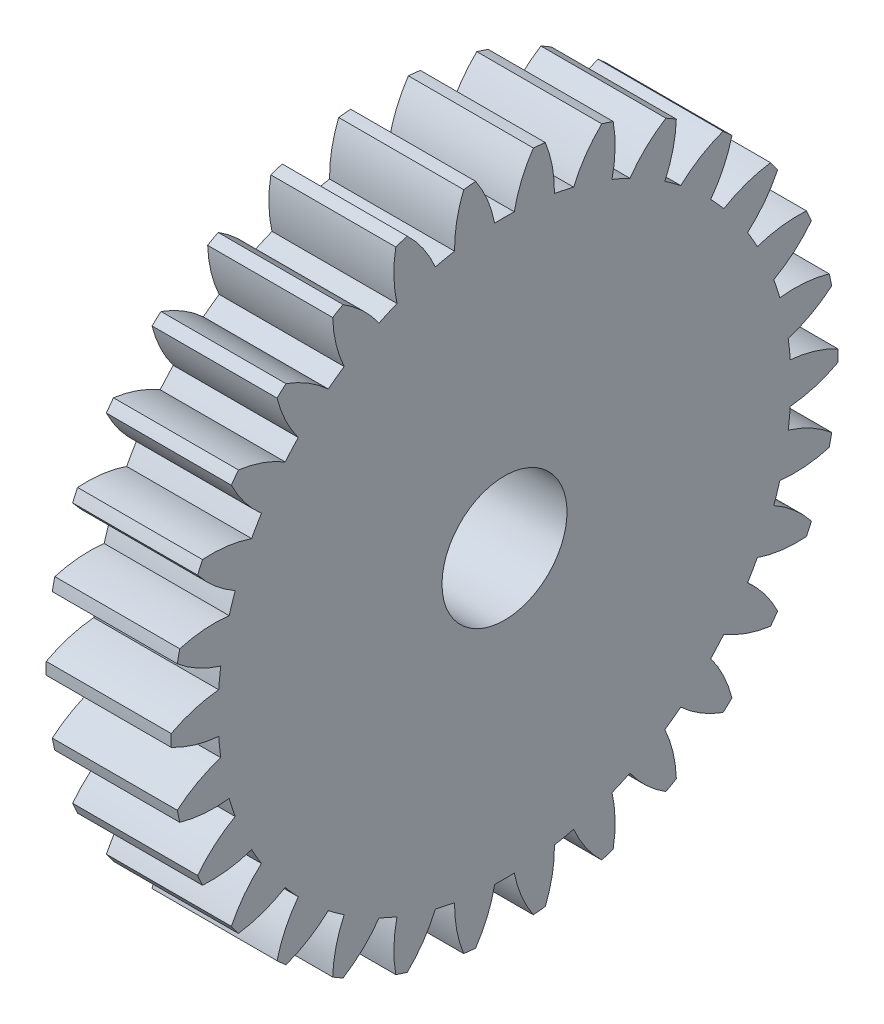
SolidWorks part; units mm, degrees
ref_plane "Plane1" through (0, 0, 0) normal (0, 0, 1) x (1, 0, 0)
ref_plane "Plane2" through (0, 0, 0) normal (0, 1, 0) x (1, 0, 0)
ref_plane "Plane3" through (0, 0, 0) normal (1, 0, 0) x (0, 0, -1)
other "Configuration Table"
sketch "HoldingSke" plane through (0, 0, 0) normal (0, 1, 0) x (1, 0, 0)
  line L0 (0, 0) -> (527.9291, -304.8)
  line L1 (-15, 0) -> (100, 0) construction
  line L2 (0, 0) -> (-2.1039, 2.3779)
  line L3 (0, 0) -> (-11.863, 4.5341)
  line L4 (0, 0) -> (7.479, 4.318)
  line L5 (0, 0) -> (-47.5972, -17.7524)
  line L6 (0, 0) -> (-5.2639, -3.5516)
  line L7 (-2.1039, 2.3779) -> (8.8308, 51.9871)
  line L8 (-76.2, 54.61) -> (-69.596, 54.61)
  line L9 (-71.009, 38.7566) -> (-53.1078, 45.2721)
  line L10 (-76.2, 71.12) -> (104.1128, 71.12)
  line L11 (0, 0) -> (-6.35, 0)
  line L12 (-76.2, 101.6) -> (-76.1573, 101.6)
  line L13 (24.9733, 27.94) -> (52.9518, 28.4284)
  line L14 (24.9733, 27.94) -> (25.0241, 27.9398)
  line L15 (24.9733, 27.94) -> (100.4021, 29.52)
  circle A0 centre (0, 0) radius 3.175
  circle A1 centre (0, 0) radius 14.5542
  circle A2 centre (0, 0) radius 38.1
  circle A3 centre (0, 0) radius 3.175
  dimension "MHD" = 29.1084
  dimension "Hub_dia" = 76.2
  dimension "Bore" = 6.35
  dimension "MBD" = 6.35
  dimension "Num_teeth" = 30
  dimension "Pitch" = 609.6
  dimension "Overall_len" = 50.8
  dimension "Show_teeth" = 30
  dimension "Thickness" = 6.35
  dimension "OAL" = 50.8001
  dimension "T_dim" = 6.604
  dimension "Ap" = 20
  dimension "H" = 19.05
  dimension "Pitch_radius" = 180.3128
  dimension "Width" = 6.35
  dimension "Backlash" = 0.0427
  dimension "Addendum_fac" = 1
  dimension "Dedendum_fac" = 1.2
  dimension "Clearance_fac" = 0.2
  dimension "Dedendum_add" = 0.0508
sketch "BasProSke" plane through (0, 0, 0) normal (0, 1, 0) x (1, 0, 0)
  line L0 (-10, 0) -> (60, 0) construction
  line L1 (0, 0) -> (0, 16.9333)
  line L2 (0, 0) -> (6.35, 0)
  line L3 (6.35, 0) -> (6.35, 16.9333)
  line L4 (6.35, 16.9333) -> (0, 16.9333)
  dimension "Thickness" = 6.35
  dimension "Diameter" = 33.8667
revolve "Base-Revolve" add sketch "BasProSke" angle 360 about L0
sketch "TooCutSke" plane through (0, 0, 0) normal (1, 0, 0) x (0, 0, -1)
  line L1 (0, 0) -> (0, 107) construction
  line L2 (0, 0) -> (-0.9055, 15.8492) construction
  line L3 (0, 0) -> (-3.315, 31.5402) construction
  line L4 (-0.9055, 15.8492) -> (-1.6575, 15.7701) construction
  arc A0 (0.4982, 14.5457) -> (-0.4982, 14.5457) centre (0, 0) ccw
  arc A1 (1.4826, 16.8938) -> (-1.4826, 16.8938) centre (0, 0) ccw
  circle A2 centre (0, 0) radius 15.875 construction
  circle A3 centre (0, 0) radius 14.9176 construction
  arc A4 (-0.4982, 14.5457) -> (-1.4826, 16.8938) centre (-6.7277, 13.3144) ccw
  arc A5 (1.4826, 16.8938) -> (0.4982, 14.5457) centre (6.7277, 13.3144) ccw
  dimension "Root_dia" = 29.1084
  dimension "Overcut_dia" = 33.9175
  dimension "Pitch_dia" = 31.75
  dimension "Base_dia" = 29.8352
  dimension "Flank_rad" = 6.35
  dimension "Half_ang" = 6
  dimension "Half_CT" = 0.7562
extrude "ToothCut" cut sketch "TooCutSke" along normal through all
fillet "Breaks" [suppressed] radius 0.0212
fillet "RootFillets" [suppressed] radius 0.2625
pattern_circular "TeethCuts" count 30 every 12 about axis through (-10, 0, 0) along (1, 0, 0) of "ToothCut", "RootFillets", "Breaks"
sketch "HubNeaOneSke" plane through (0, 0, 0) normal (-1, 0, 0) x (0, 0, 1)
  circle A0 centre (0, 0) radius 14.5542
  dimension "Diameter" = 29.1084
extrude "HubNearOne" [suppressed] add sketch "HubNeaOneSke" along normal blind 44.4501
sketch "HubNeaBotSke" plane through (0, 0, 0) normal (-1, 0, 0) x (0, 0, 1)
  circle A0 centre (0, 0) radius 14.5542
  dimension "Diameter" = 29.1084
extrude "HubNearBoth" [suppressed] add sketch "HubNeaBotSke" along normal blind 22.225
ref_plane "FarPln" through (6.35, 0, 0) normal (1, 0, 0) x (0, 0, -1)
sketch "HubFarSke" plane through (6.35, 0, 0) normal (1, 0, 0) x (0, 0, -1)
  circle A0 centre (0, 0) radius 14.5542
  dimension "Diameter" = 29.1084
extrude "HubFar" [suppressed] add sketch "HubFarSke" along normal blind 22.225
sketch "BorSke" plane through (0, 0, 0) normal (1, 0, 0) x (0, 0, -1)
  circle A0 centre (0, 0) radius 3.175
  dimension "Diameter" = 6.35
extrude "Bore" cut sketch "BorSke" along normal mid plane 101.6001
sketch "KeySke" plane through (0, 0, 0) normal (1, 0, 0) x (0, 0, -1)
  line L0 (-0.127, 0) -> (-0.127, 3.429)
  line L1 (-0.127, 3.429) -> (0.127, 3.429)
  line L2 (0.127, 3.429) -> (0.127, 0)
  line L3 (0, 0) -> (0, 34) construction
  line L4 (-0.127, 0) -> (0.127, 0)
  dimension "Offset" = 3.429
  dimension "Width" = 0.254
extrude "Keyway" [suppressed] cut sketch "KeySke" along normal mid plane 101.6001
pattern_circular "Keyway2" [suppressed] count 2 every 90 about axis through (-10, 0, 0) along (1, 0, 0)
equation "' \"Pitch@HoldingSke\" = 4"
equation "' \"Num_teeth@HoldingSke\" = 12"
equation "' \"Ap@HoldingSke\" =  20"
equation "' \"Ap@HoldingSke\" = 20"
equation "' \"Width@HoldingSke\" = 0.5"
equation "' \"Hub_dia@HoldingSke\"= 1"
equation "' \"Hub_dia@HoldingSke\" = 1"
equation "' \"Overall_len@HoldingSke\" = 1.0"
equation "' \"Bore@HoldingSke\" = 0.75"
equation "' \"T_dim@HoldingSke\" = 0.85"
equation "' \"Width@KeySke\" = 0.25"
equation "' \"Show_teeth@HoldingSke\" = 13"
equation "' \"Backlash@HoldingSke\" = 0.009"
equation "' \"Addendum_fac@HoldingSke\" = 1.0"
equation "' \"Dedendum_fac@HoldingSke\" = 1.25"
equation "' \"Dedendum_add@HoldingSke\" = 0.00005"
equation "' \"Clearance_fac@HoldingSke\" = 0.25"
equation "' \"Pitch@HoldingSke\" = 0.5"
equation "' \"Num_teeth@HoldingSke\" = 23"
equation "' \"Show_teeth@HoldingSke\" = 23"
equation "' \"Backlash@HoldingSke\" = 0.0375"
equation "\"Overcut_dia@TooCutSke\" = (\"Num_teeth@HoldingSke\" + 2 * \"Addendum_fac@HoldingSke\") / \"Pitch@HoldingSke\" + 0.002"
equation "\"Pitch_dia@TooCutSke\" = \"Num_teeth@HoldingSke\" / \"Pitch@HoldingSke\""
equation "\"Base_dia@TooCutSke\" = \"Num_teeth@HoldingSke\" / \"Pitch@HoldingSke\" * cos((\"Ap@HoldingSke\"  * 3.14159265 / 180))"
equation "\"Root_dia@TooCutSke\" = (\"Num_teeth@HoldingSke\" + 2) / \"Pitch@HoldingSke\" - 2 * (\"Addendum_fac@HoldingSke\" + \"Dedendum_fac@HoldingSke\") / \"Pitch@HoldingSke\" - \"Dedendum_add@HoldingSke\" * 2"
equation "\"Half_ang@TooCutSke\" = 180 / \"Num_teeth@HoldingSke\""
equation "\"Half_CT@TooCutSke\" = \"Num_teeth@HoldingSke\" / \"Pitch@HoldingSke\" * sin((3.14159265 / 2 / \"Num_teeth@HoldingSke\")) / 2 - 7 * \"Backlash@HoldingSke\" / 4"
equation "\"Flank_rad@TooCutSke\" = \"Num_teeth@HoldingSke\" / \"Pitch@HoldingSke\" / 5"
equation "\"Radius@RootFillets\" = \"Clearance_fac@HoldingSke\" / \"Pitch@HoldingSke\" + \"Dedendum_add@HoldingSke\""
equation "\"Break_rad@Breaks\" = 0.02 / \"Pitch@HoldingSke\""
equation "\"Thickness@HoldingSke\" = \"Width@HoldingSke\""
equation "\"OAL@HoldingSke\" = \"Thickness@HoldingSke\""
equation "\"MHD@HoldingSke\" = (\"Num_teeth@HoldingSke\" + 2) / \"Pitch@HoldingSke\" - 2 * (\"Addendum_fac@HoldingSke\" + \"Dedendum_fac@HoldingSke\")  / \"Pitch@HoldingSke\" - \"Dedendum_add@HoldingSke\" * 2"
equation "\"MBD@HoldingSke\" = (\"Num_teeth@HoldingSke\" + 2) / \"Pitch@HoldingSke\" - 2 * (\"Addendum_fac@HoldingSke\" + \"Dedendum_fac@HoldingSke\")  / \"Pitch@HoldingSke\" - \"Dedendum_add@HoldingSke\" * 2 - 0.002"
equation "\"MHD@HoldingSke\" = ((sgn( \"MHD@HoldingSke\" - \"Hub_dia@HoldingSke\" )-1)*( \"MHD@HoldingSke\" - \"Hub_dia@HoldingSke\" ))/-2+ \"Hub_dia@HoldingSke\""
equation "\"MBD@HoldingSke\" = ((sgn( \"MBD@HoldingSke\" - \"Bore@HoldingSke\" )-1)*( \"MBD@HoldingSke\" - \"Bore@HoldingSke\" ))/-2+ \"Bore@HoldingSke\""
equation "\"OAL@HoldingSke\" = ((sgn( \"OAL@HoldingSke\" - \"Overall_len@HoldingSke\" )+1)*( \"OAL@HoldingSke\" - \"Overall_len@HoldingSke\" ))/2 + \"Overall_len@HoldingSke\" + 0.000002"
equation "\"Num_teeth@TeethCuts\" = int( \"Show_teeth@HoldingSke\" ) + 1"
equation "\"Num_teeth@TeethCuts\" = ((sgn( \"Num_teeth@TeethCuts\" - \"Num_teeth@HoldingSke\" )-1)*( \"Num_teeth@TeethCuts\" - \"Num_teeth@HoldingSke\" ))/-2+ \"Num_teeth@HoldingSke\""
equation "\"Num_teeth@TeethCuts\" = ((sgn( \"Num_teeth@TeethCuts\" - 2.0)+1)*( \"Num_teeth@TeethCuts\" - 2.0))/2 +2.0"
equation "\"Angle@TeethCuts\" = 360.0 / \"Num_teeth@HoldingSke\""
equation "\"Diameter@BasProSke\" = (\"Num_teeth@HoldingSke\" + 2 * \"Addendum_fac@HoldingSke\") / \"Pitch@HoldingSke\""
equation "\"Thickness@BasProSke\"  = \"Thickness@HoldingSke\""
equation "' \"Fillet_rad@BasProSke\" =  \"Thickness@HoldingSke\" * 0.05"
equation "' \"Fillet_rad@BasProSke\" = \"Thickness@HoldingSke\" * 0.05"
equation "\"MHD@HoldingSke\" = ((sgn( \"MHD@HoldingSke\" - \"Root_dia@TooCutSke\" )-1)*( \"MHD@HoldingSke\" - \"Root_dia@TooCutSke\" ))/-2+ \"Root_dia@TooCutSke\""
equation "\"Diameter@HubNeaOneSke\" = \"MHD@HoldingSke\""
equation "\"Length@HubNearOne\" = \"OAL@HoldingSke\" - \"Thickness@BasProSke\""
equation "\"Diameter@HubNeaBotSke\" = \"MHD@HoldingSke\""
equation "\"Length@HubNearBoth\" = ( \"OAL@HoldingSke\" - \"Thickness@BasProSke\" ) / 2.0"
equation "\"Thickness@FarPln\" = \"Thickness@BasProSke\""
equation "\"Diameter@HubFarSke\" = \"MHD@HoldingSke\""
equation "\"Length@HubFar\" = ( \"OAL@HoldingSke\" - \"Thickness@BasProSke\" ) / 2.0"
equation "\"Diameter@BorSke\" = \"MBD@HoldingSke\""
equation "\"D1@Bore\" = \"OAL@HoldingSke\" * 2.0"
equation "\"D1@Keyway\" = \"OAL@HoldingSke\" * 2.0"
equation "\"Offset@KeySke\" = \"T_dim@HoldingSke\" - \"MBD@HoldingSke\" / 2.0"
